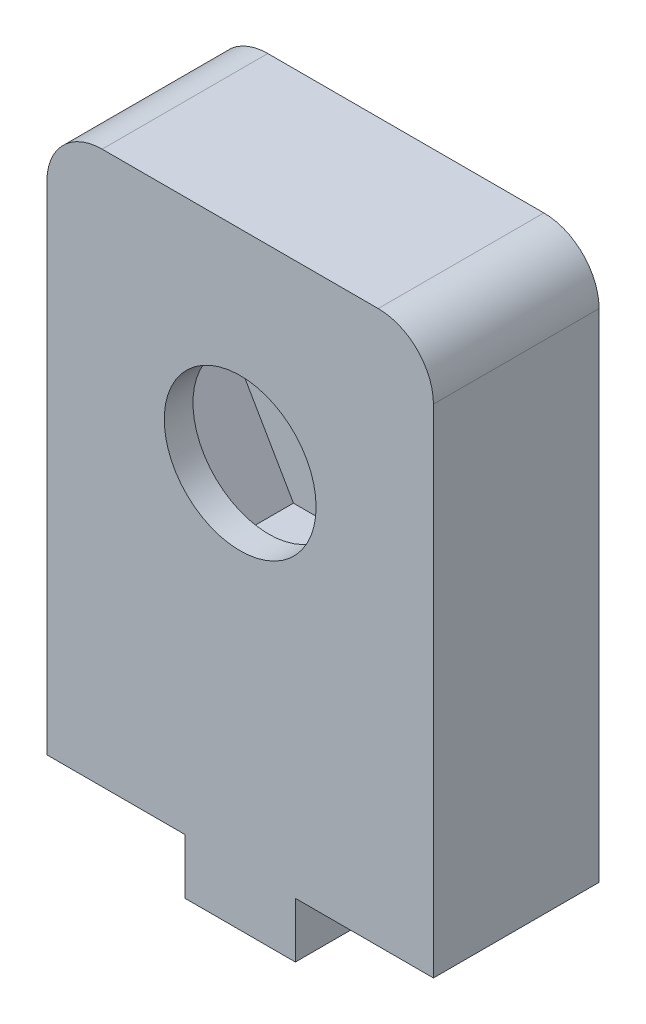
SolidWorks part; units mm, degrees
ref_plane "Front Plane" through (0, 0, 0) normal (0, 0, 1) x (1, 0, 0)
ref_plane "Top Plane" through (0, 0, 0) normal (0, 1, 0) x (1, 0, 0)
ref_plane "Right Plane" through (0, 0, 0) normal (1, 0, 0) x (0, 0, -1)
sketch "Sketch1" plane through (0, 0, 0) normal (0, 0, 1) x (1, 0, 0)
  line L0 (-1, -5) -> (-1, -6)
  line L1 (-2.5, 5) -> (2.5, 5)
  line L2 (-3.5, 4) -> (-3.5, -5)
  line L3 (-3.5, -5) -> (-1, -5)
  line L4 (3.5, 4) -> (3.5, -5)
  line L5 (-3.5, 5) -> (3.5, -5) construction
  line L6 (-3.5, -5) -> (3.5, 5) construction
  line L7 (-1, -6) -> (1, -6)
  line L8 (1, -6) -> (1, -5)
  line L9 (1, -5) -> (3.5, -5)
  arc A0 (3.5, 4) -> (2.5, 5) centre (2.5, 4) ccw
  arc A1 (-2.5, 5) -> (-3.5, 4) centre (-2.5, 4) ccw
  circle A2 centre (0, 1.325) radius 1.375
  point P0 (0, 0)
  point P18 (0, 0)
  point P19 (0, 5)
  dimension "D3" = 1
  dimension "D6" = 2.75
  dimension "D1" = 9
  dimension "D2" = 7
  dimension "D4" = 2
  dimension "D5" = 1
  dimension "D7" = 3.675
extrude "Boss-Extrude1" add sketch "Sketch1" along normal blind 3
ref_plane "Plane1" through (0, 0, 1.5) normal (0, 0, 1) x (1, 0, 0)
sketch "Sketch2" plane through (0, 0, 1.5) normal (0, 0, 1) x (1, 0, 0)
  line L0 (2.5, 5) -> (-2.5, 5) construction
  line L1 (3.0311, 1.325) -> (1.5155, 3.95)
  line L2 (1.5155, 3.95) -> (-1.5155, 3.95)
  line L3 (-1.5155, 3.95) -> (-3.0311, 1.325)
  line L4 (-3.0311, 1.325) -> (-1.5155, -1.3)
  line L5 (-1.5155, -1.3) -> (1.5155, -1.3)
  line L6 (1.5155, -1.3) -> (3.0311, 1.325)
  circle A0 centre (0, 1.325) radius 2.625 construction
  point P1 (3.0257, 1.1436)
  dimension "D1" = 5.25
extrude "Cut-Extrude1" cut sketch "Sketch2" against normal mid plane 1.96
